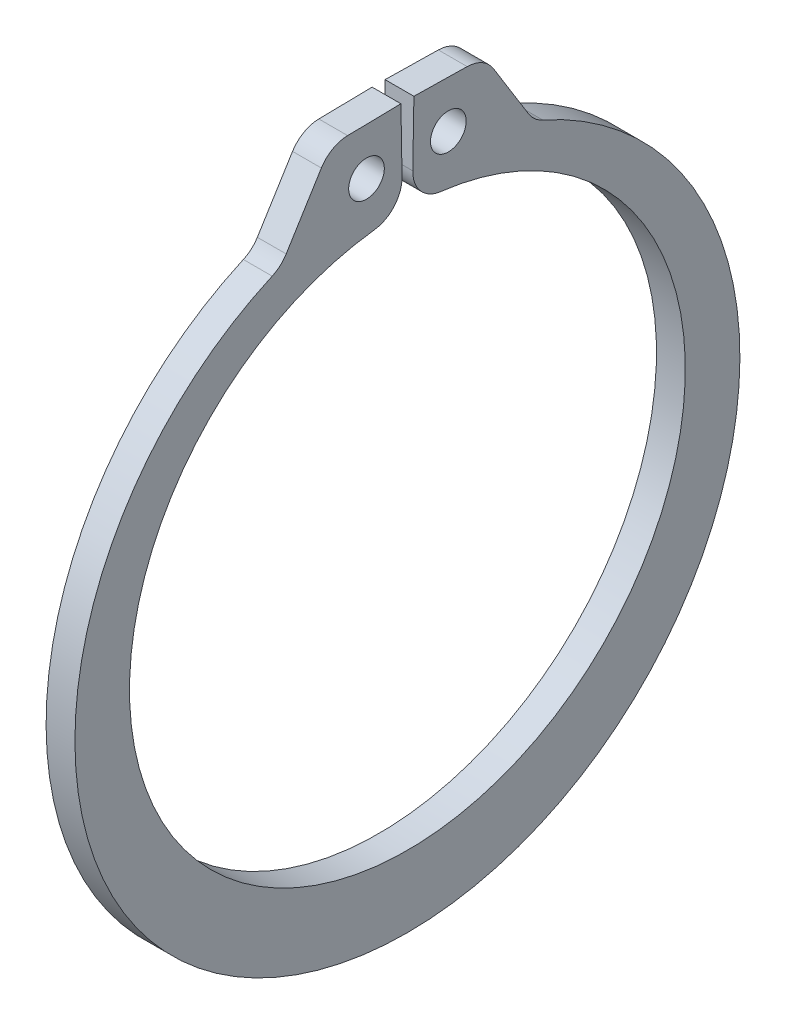
SolidWorks part; units mm, degrees
material "Cast Carbon Steel"
ref_plane "Front" through (0, 0, 0) normal (0, 0, 1) x (1, 0, 0)
ref_plane "Top" through (0, 0, 0) normal (0, 1, 0) x (1, 0, 0)
ref_plane "Right" through (0, 0, 0) normal (1, 0, 0) x (0, 0, -1)
sketch "Sketch1" plane through (0, 0, 0) normal (1, 0, 0) x (0, 0, -1)
  line L0 (0, 0) -> (0, 10.287) construction
  line L1 (-0.1795, 10.2854) -> (-0.2403, 13.7647)
  line L2 (0.2403, 13.7647) -> (2.8497, 13.7192)
  line L3 (2.8497, 13.7192) -> (4.6815, 10.7605)
  line L4 (0.1795, 10.2854) -> (0.2403, 13.7647)
  line L5 (-0.2403, 13.7647) -> (-2.8497, 13.7192)
  line L6 (-2.8497, 13.7192) -> (-4.6815, 10.7605)
  line L7 (-4.6815, 10.7605) -> (-4.1039, 9.4329) construction
  line L8 (4.6815, 10.7605) -> (4.1039, 9.4329) construction
  line L9 (0, -10.287) -> (0, -12.9286) construction
  line L10 (-2.8497, 13.7192) -> (-0.1795, 10.2854) construction
  line L11 (0, 10.287) -> (0, 13.7668) construction
  line L12 (-10.287, 0) -> (10.287, 0) construction
  circle A0 centre (0, 0) radius 10.287 construction
  arc A1 (-0.1795, 10.2854) -> (0.1795, 10.2854) centre (0, 0) ccw
  circle A4 centre (-1.5146, 12.0023) radius 0.6604
  circle A5 centre (1.5146, 12.0023) radius 0.6604
  arc A6 (-4.6815, 10.7605) -> (4.6815, 10.7605) centre (0, -0.6214) ccw construction
  point P0 (0, -12.9286)
  dimension "Ring ID" = 20.574
  dimension "Hole Diameter" = 1.3208
  dimension "Min. Sec." = 1.4478
  dimension "Max. Sec." = 2.6416
  dimension "Lug Height" = 3.4798
  dimension "D2" = 2.6098
  dimension "Angle" = 1
sketch "Sketch2" plane through (0, 0, 0) normal (0, 1, 0) x (1, 0, 0)
  line L0 (-0.5334, -12.2915) -> (0.5334, -12.2915) construction
  line L1 (0, -12.3072) -> (0, 12.3072) construction
  point P8 (0, -12.2915)
  dimension "Ring Thickness" = 1.0668
sketch "Sketch3" plane through (0, 0, 0) normal (1, 0, 0) x (0, 0, -1)
  line L0 (-2.8497, 13.7192) -> (-4.6815, 10.7605) construction
  line L1 (-2.8497, 13.7192) -> (-4.6815, 10.7605)
  line L2 (-0.2403, 13.7647) -> (-2.8497, 13.7192) construction
  line L3 (-0.2403, 13.7647) -> (-2.8497, 13.7192)
  line L4 (-0.1795, 10.2854) -> (-0.2403, 13.7647) construction
  line L5 (-0.1795, 10.2854) -> (-0.2403, 13.7647)
  line L6 (0.1795, 10.2854) -> (0.2403, 13.7647) construction
  line L7 (0.1795, 10.2854) -> (0.2403, 13.7647)
  line L8 (0.2403, 13.7647) -> (2.8497, 13.7192) construction
  line L9 (0.2403, 13.7647) -> (2.8497, 13.7192)
  line L10 (2.8497, 13.7192) -> (4.6815, 10.7605) construction
  line L11 (2.8497, 13.7192) -> (4.6815, 10.7605)
  arc A0 (-4.6815, 10.7605) -> (4.6815, 10.7605) centre (0, -0.6214) ccw construction
  arc A1 (-4.6815, 10.7605) -> (4.6815, 10.7605) centre (0, -0.6214) ccw
  arc A2 (-0.1795, 10.2854) -> (0.1795, 10.2854) centre (0, 0) ccw construction
  arc A3 (-0.1795, 10.2854) -> (0.1795, 10.2854) centre (0, 0) ccw
  circle A4 centre (-1.5146, 12.0023) radius 0.6604 construction
  circle A5 centre (-1.5146, 12.0023) radius 0.6604
  circle A6 centre (1.5146, 12.0023) radius 0.6604 construction
  circle A7 centre (1.5146, 12.0023) radius 0.6604
extrude "Boss-Extrude1" add sketch "Sketch3" along normal up to vertex (0.5334 mm away) and the other way up to vertex (0.5334 mm away) up to point (0.5334, 0, 12.2915) other way up to point (-0.5334, 0, 12.2915)
fillet "Fillet1" radius 1.1684 6 edges at (0, 10.7605, -4.6815) (0, 13.7192, -2.8497) (0, 10.2854, -0.1795) (0, 10.2854, 0.1795) (0, 13.7192, 2.8497) (0, 10.7605, 4.6815)
sketch "Sketch4" plane through (0, 0, 0) normal (1, 0, 0) x (0, 0, -1)
  line L0 (-8.9088, 5.1435) -> (0, 0) construction
  line L1 (0, 0) -> (0, 10.287) construction
  line L2 (0, 13.7668) -> (0, 10.287) construction
  arc A0 (-0.1795, 10.2854) -> (0.1795, 10.2854) centre (0, 0) ccw construction
  point P0 (0, 0)
  point P1 (-8.9088, 5.1435)
  dimension "D1" = 60
equation "\"D2@Sketch1\" = \"Lug Height@Sketch1\" * .75"
